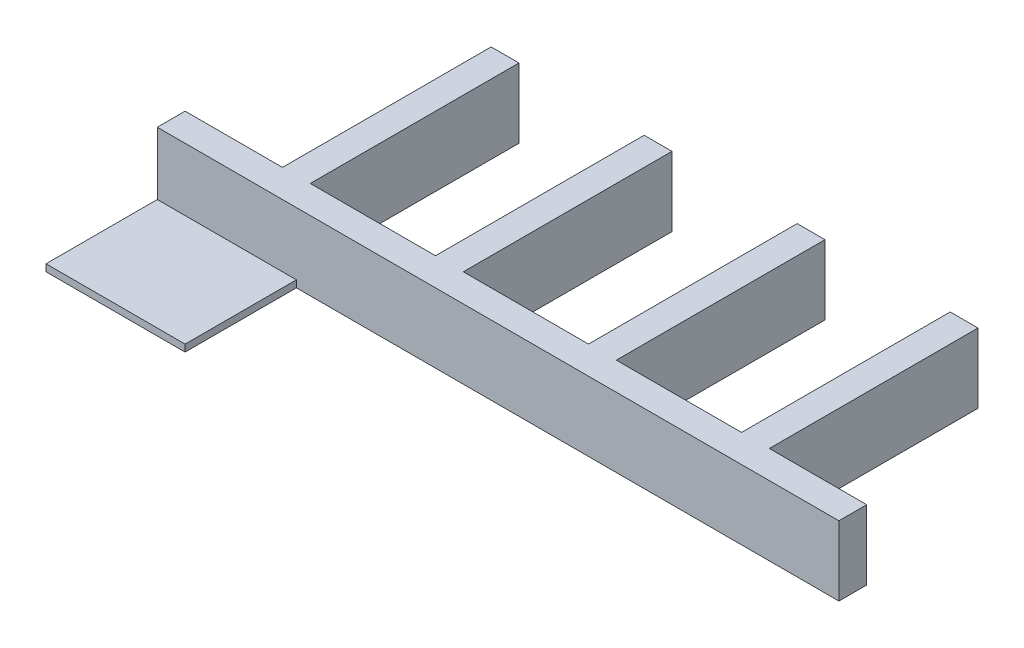
SolidWorks part; units mm, degrees
ref_plane "Спереди" through (0, 0, 0) normal (0, 0, 1) x (1, 0, 0)
ref_plane "Сверху" through (0, 0, 0) normal (0, 1, 0) x (1, 0, 0)
ref_plane "Справа" through (0, 0, 0) normal (1, 0, 0) x (0, 0, -1)
sketch "Sketch1" plane through (0, 0, 0) normal (0, 1, 0) x (1, 0, 0)
  line L0 (0, 0) -> (490, 0)
  line L1 (490, 0) -> (490, 20)
  line L2 (490, 20) -> (420, 20)
  line L3 (0, 20) -> (0, 0)
  line L4 (70, 170) -> (70, 20)
  line L5 (70, 170) -> (90, 170)
  line L6 (90, 170) -> (90, 20)
  line L7 (180, 20) -> (180, 170)
  line L8 (180, 170) -> (200, 170)
  line L9 (200, 170) -> (200, 20)
  line L10 (290, 20) -> (290, 170)
  line L11 (290, 170) -> (310, 170)
  line L12 (310, 170) -> (310, 20)
  line L13 (400, 20) -> (400, 170)
  line L14 (400, 170) -> (420, 170)
  line L15 (420, 170) -> (420, 20)
  line L16 (70, 20) -> (0, 20)
  line L17 (180, 20) -> (90, 20)
  line L18 (290, 20) -> (200, 20)
  line L19 (400, 20) -> (310, 20)
  dimension "D1" = 490
  dimension "D2" = 20
  dimension "D3" = 20
  dimension "D4" = 150
  dimension "D5" = 20
  dimension "D6" = 20
  dimension "D7" = 20
  dimension "D8" = 70
  dimension "D9" = 70
  dimension "D10" = 180
  dimension "D11" = 180
extrude "Boss-Extrude1" add sketch "Sketch1" along normal blind 50
sketch "Sketch2" plane through (0, 0, 0) normal (0, 0, 1) x (1, 0, 0)
  line L0 (0, 0) -> (0, 5)
  line L1 (0, 50) -> (0, 0) construction
  line L2 (0, 5) -> (100, 5)
  line L3 (100, 5) -> (100, 0)
  line L4 (0, 0) -> (490, 0) construction
  line L5 (100, 0) -> (0, 0)
  dimension "D1" = 100
  dimension "D2" = 5
extrude "Boss-Extrude2" add sketch "Sketch2" along normal blind 80
